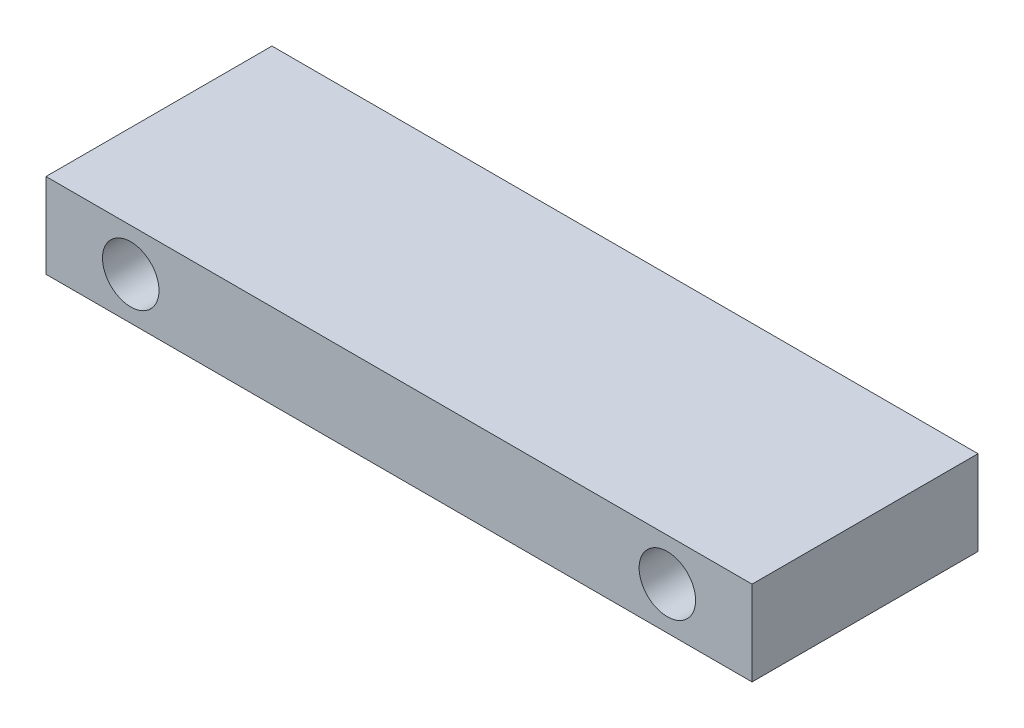
SolidWorks part; units mm, degrees
ref_plane "Front Plane" through (0, 0, 0) normal (0, 0, 1) x (1, 0, 0)
ref_plane "Top Plane" through (0, 0, 0) normal (0, 1, 0) x (1, 0, 0)
ref_plane "Right Plane" through (0, 0, 0) normal (1, 0, 0) x (0, 0, -1)
sketch "Sketch1" plane through (0, 0, 0) normal (0, 0, 1) x (1, 0, 0)
  line L0 (-93.1728, 35.3095) -> (-68.1728, 35.3095)
  line L1 (-68.1728, 35.3095) -> (-68.1728, 32.3095)
  line L2 (-68.1728, 32.3095) -> (-93.1728, 32.3095)
  line L3 (-93.1728, 32.3095) -> (-93.1728, 35.3095)
  circle A0 centre (-90.1728, 33.8095) radius 1
  circle A1 centre (-71.1728, 33.8095) radius 1
extrude "Boss-Extrude1" add sketch "Sketch1" along normal blind 8
